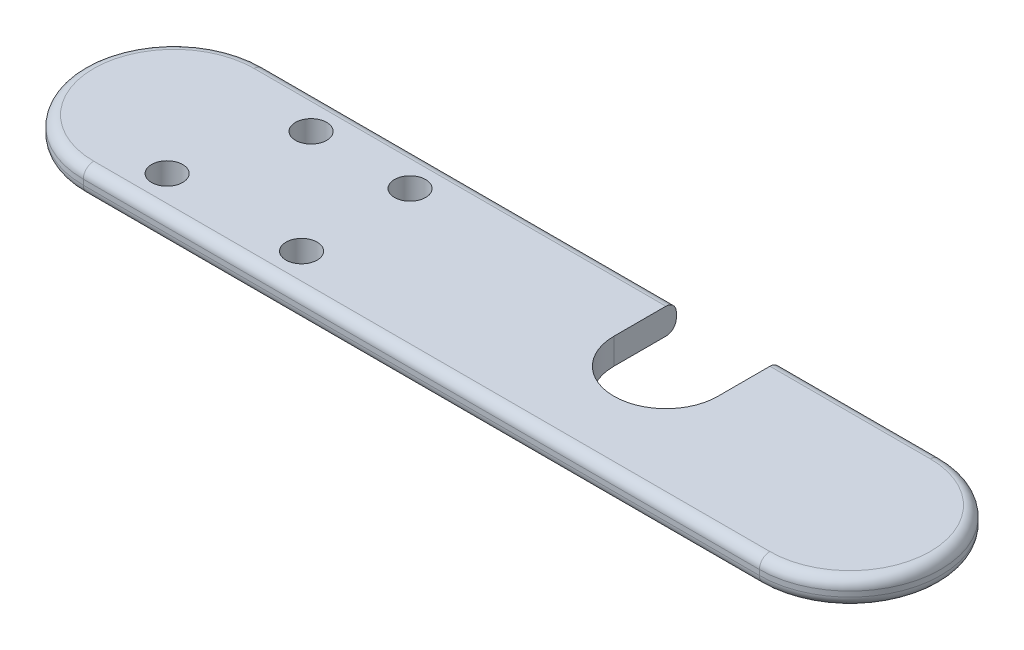
SolidWorks part; units mm, degrees
ref_plane "Front Plane" through (0, 0, 0) normal (0, 0, 1) x (1, 0, 0)
ref_plane "Top Plane" through (0, 0, 0) normal (0, 1, 0) x (1, 0, 0)
ref_plane "Right Plane" through (0, 0, 0) normal (1, 0, 0) x (0, 0, -1)
sketch "Sketch1" plane through (0, 0, 0) normal (0, 1, 0) x (1, 0, 0)
  line L0 (-65.005, 0) -> (65.005, 0) construction
  line L1 (-65.005, 17.43) -> (65.005, 17.43)
  line L2 (-65.005, -17.43) -> (65.005, -17.43)
  line L3 (-82.435, 0) -> (82.435, 0) construction
  arc A0 (-65.005, 17.43) -> (-65.005, -17.43) centre (-65.005, 0) ccw
  arc A1 (65.005, -17.43) -> (65.005, 17.43) centre (65.005, 0) ccw
  point P2 (0, 0)
  dimension "D1" = 164.87
  dimension "D2" = 34.86
extrude "Boss-Extrude1" add sketch "Sketch1" along normal mid plane 5
sketch "Sketch2" plane through (0, 2.5, 0) normal (0, 1, 0) x (1, 0, 0)
  line L0 (-82.435, 0) -> (-82.435, 33.2924) construction
  line L3 (65.005, 17.43) -> (-65.005, 17.43) construction
  line L4 (-65.005, -17.43) -> (65.005, -17.43) construction
  circle A0 centre (-49.065, 10.43) radius 3
  circle A1 centre (-30.035, 10.43) radius 3
  circle A2 centre (-55.895, -10.43) radius 3
  circle A3 centre (-30.035, -10.43) radius 3
  arc A4 (-65.005, 17.43) -> (-65.005, -17.43) centre (-65.005, 0) ccw construction
  dimension "D1" = 6
  dimension "D2" = 6
  dimension "D3" = 6
  dimension "D4" = 6
  dimension "D5" = 52.4
  dimension "D6" = 33.37
  dimension "D7" = 26.54
  dimension "D8" = 7
  dimension "D9" = 7
extrude "Cut-Extrude1" cut sketch "Sketch2" against normal up to next
fillet "Fillet1" radius 2 8 edges at (0, 2.5, -17.43) (82.435, 2.5, 0) (0, -2.5, -17.43) (82.435, -2.5, 0) (0, 2.5, 17.43) (0, -2.5, 17.43) (-82.435, 2.5, 0) (-82.435, -2.5, 0)
sketch "Sketch3" plane through (0, 2.5, 0) normal (0, 1, 0) x (1, 0, 0)
  line L0 (34.165, 17.43) -> (34.165, 5.43)
  line L1 (-65.005, 17.43) -> (65.005, 17.43) construction
  line L2 (34.165, 17.43) -> (14.165, 17.43)
  line L3 (14.165, 17.43) -> (14.165, 5.43)
  line L4 (-82.435, 0) -> (-82.435, -27.3775) construction
  arc A0 (34.165, 5.43) -> (14.165, 5.43) centre (24.165, 5.43) cw
  arc A1 (-65.005, 17.43) -> (-65.005, -17.43) centre (-65.005, 0) ccw construction
  dimension "D1" = 20
  dimension "D2" = 96.6
  dimension "D3" = 12
extrude "Cut-Extrude2" cut sketch "Sketch3" against normal blind 10
equation "\"hole d\"= 6"
equation "\"top left from front\"= 33.37"
equation "\"bottom left from front\"= 26.54"
equation "\"right  from front - back of hole\"= 55.4"
equation "\"from side\"= 7"
equation "\"D1@Sketch2\"=\"hole d\""
equation "\"D2@Sketch2\"=\"D1@Sketch2\""
equation "\"D3@Sketch2\"=\"D1@Sketch2\""
equation "\"D4@Sketch2\"=\"D3@Sketch2\""
equation "\"D5@Sketch2\"=\"right  from front - back of hole\"-\"hole d\"/2"
equation "\"D6@Sketch2\"=\"top left from front\""
equation "\"D7@Sketch2\"=\"bottom left from front\""
equation "\"D8@Sketch2\"=\"from side\""
equation "\"D9@Sketch2\"=\"D8@Sketch2\""
